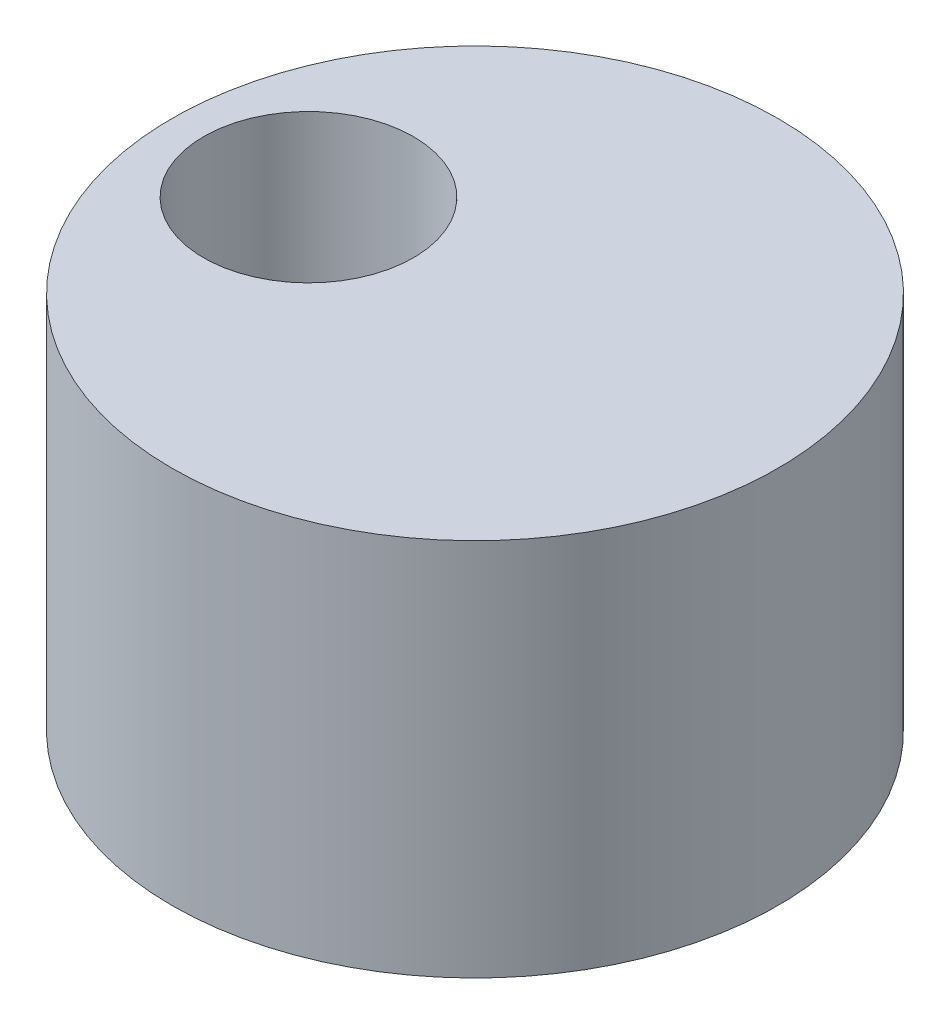
SolidWorks part; units mm, degrees
ref_plane "Front Plane" through (0, 0, 0) normal (0, 0, 1) x (1, 0, 0)
ref_plane "Top Plane" through (0, 0, 0) normal (0, 1, 0) x (1, 0, 0)
ref_plane "Right Plane" through (0, 0, 0) normal (1, 0, 0) x (0, 0, -1)
sketch "Sketch1" plane through (0, 0, 0) normal (0, 1, 0) x (1, 0, 0)
  circle A0 centre (0, 0) radius 6.35
  dimension "D1" = 12.7
extrude "Boss-Extrude1" add sketch "Sketch1" along normal blind 7.9375
sketch "Sketch2" plane through (0, 0, 0) normal (0, -1, 0) x (1, 0, 0)
  line L0 (-3.49, 0) -> (-3.49, 2.54) construction
  line L1 (-3.49, 0) -> (-3.49, -2.54) construction
  line L2 (-6.35, 0) -> (6.35, 0) construction
  circle A1 centre (-3.49, 2.54) radius 2 construction
  circle A2 centre (-3.49, -2.54) radius 2 construction
  circle A3 centre (0, 0) radius 6.35 construction
  circle A4 centre (-3.49, 0) radius 2.2
  dimension "D1" = 2.86
  dimension "D4" = 4
  dimension "D5" = 4.4
  dimension "D2" = 5.08
extrude "Cut-Extrude1" cut sketch "Sketch2" against normal through all
sketch "Sketch3" plane through (0, 0, 0) normal (0, -1, 0) x (1, 0, 0)
  line L0 (-3.49, -2.2) -> (-3.49, -3.8) construction
  line L1 (-3.49, 2.2) -> (-3.49, 3.8) construction
  circle A0 centre (-3.49, 0) radius 2.2 construction
  circle A1 centre (-3.49, 0) radius 2.2 construction
  circle A2 centre (-3.49, -3.8) radius 1
  circle A3 centre (-3.49, 3.8) radius 1
  dimension "D2" = 2
  dimension "D1" = 1.6
extrude "Cut-Extrude2" cut sketch "Sketch3" against normal blind 3.4
